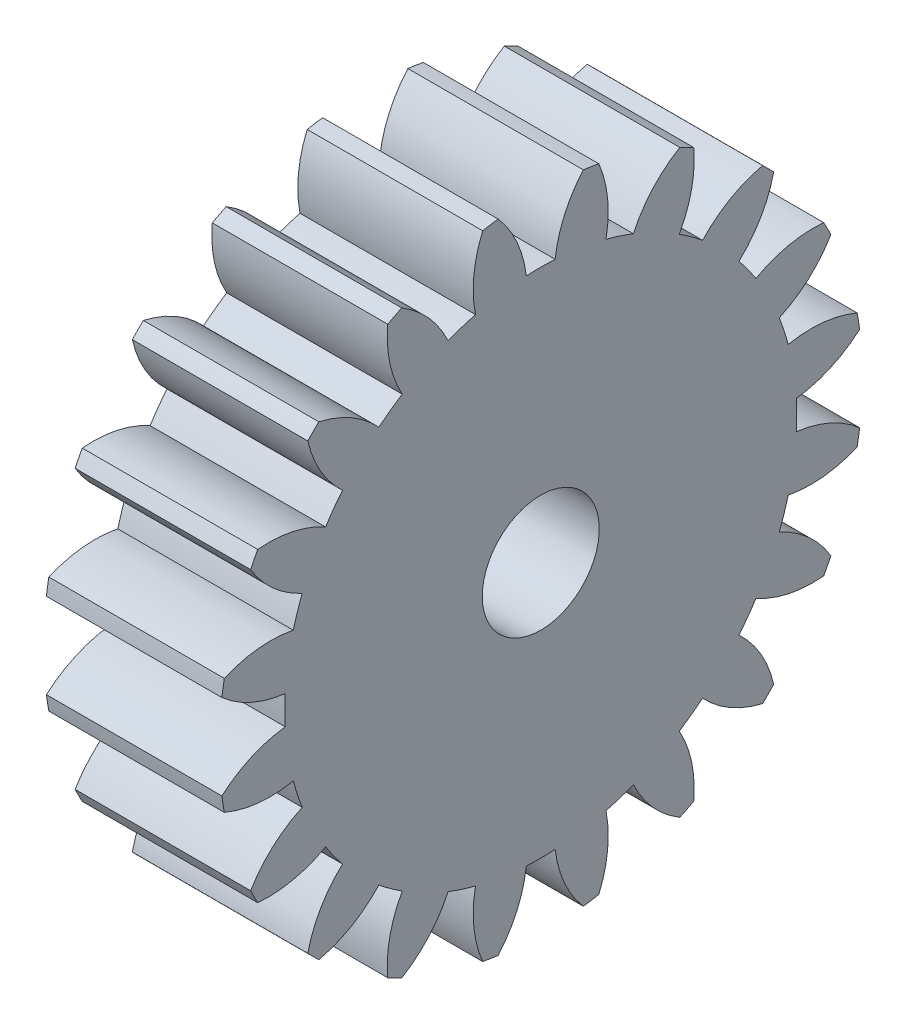
SolidWorks part; units mm, degrees
ref_plane "Plane1" through (0, 0, 0) normal (0, 0, 1) x (1, 0, 0)
ref_plane "Plane2" through (0, 0, 0) normal (0, 1, 0) x (1, 0, 0)
ref_plane "Plane3" through (0, 0, 0) normal (1, 0, 0) x (0, 0, -1)
sketch "HoldingSke" plane through (0, 0, 0) normal (0, 1, 0) x (1, 0, 0)
  line L0 (0, 0) -> (0.1879, -0.0684)
  line L1 (-15, 0) -> (100, 0) construction
  line L2 (0, 0) -> (-2.1039, 2.3779)
  line L3 (0, 0) -> (-11.863, 4.5341)
  line L4 (0, 0) -> (8.1152, 2.9537)
  line L5 (0, 0) -> (-46.8476, -17.4728)
  line L6 (0, 0) -> (-24.8689, -16.7791)
  line L7 (-2.1039, 2.3779) -> (8.6586, 51.2059)
  line L8 (-76.2, 54.61) -> (-73.4, 54.61)
  line L9 (-71.009, 38.7566) -> (-53.1078, 45.2721)
  line L10 (-76.2, 71.12) -> (104.1128, 71.12)
  line L11 (0, 0) -> (-30, 0)
  line L12 (-76.2, 101.6) -> (-76.033, 101.6)
  line L13 (24.9733, 27.94) -> (52.9518, 28.4284)
  line L14 (24.9733, 27.94) -> (24.9743, 27.94)
  line L15 (24.9733, 27.94) -> (100.4006, 29.5858)
  line L16 (-63.627, -5) -> (-12.827, -5)
  circle A0 centre (0, 0) radius 10
  circle A1 centre (0, 0) radius 37.5
  circle A2 centre (0, 0) radius 37.5
  circle A3 centre (0, 0) radius 10
  dimension "MHD" = 75
  dimension "Hub_dia" = 75
  dimension "Bore" = 20
  dimension "MBD" = 20
  dimension "Num_teeth" = 20
  dimension "Pitch" = 0.2
  dimension "Overall_len" = 50
  dimension "Show_teeth" = 20
  dimension "Thickness" = 30
  dimension "OAL" = 50.0001
  dimension "T_dim" = 2.8
  dimension "Ap" = 20
  dimension "H" = 19.05
  dimension "Pitch_radius" = 180.3128
  dimension "Width" = 30
  dimension "Backlash" = 0.167
  dimension "Addendum_fac" = 1
  dimension "Dedendum_fac" = 1.25
  dimension "Clearance_fac" = 0.25
  dimension "Dedendum_add" = 0.001
  dimension "Module" = 5
sketch "BasProSke" plane through (0, 0, 0) normal (0, 1, 0) x (1, 0, 0)
  line L0 (-10, 0) -> (60, 0) construction
  line L1 (0, 0) -> (0, 55)
  line L2 (0, 0) -> (30, 0)
  line L3 (30, 0) -> (30, 55)
  line L4 (30, 55) -> (0, 55)
  dimension "Thickness" = 30
  dimension "Diameter" = 110
revolve "Base-Revolve" add sketch "BasProSke" angle 360 about L0
sketch "TooCutSke" plane through (0, 0, 0) normal (1, 0, 0) x (0, 0, -1)
  line L1 (0, 0) -> (0, 107) construction
  line L2 (0, 0) -> (-4.2151, 49.822) construction
  line L3 (0, 0) -> (-15.6021, 98.5081) construction
  line L4 (-4.2151, 49.822) -> (-7.8011, 49.254) construction
  arc A0 (2.4648, 43.6795) -> (-2.4648, 43.6795) centre (0, 0) ccw
  arc A1 (7.3009, 54.5389) -> (-7.3009, 54.5389) centre (0, 0) ccw
  circle A2 centre (0, 0) radius 50 construction
  circle A3 centre (0, 0) radius 46.9846 construction
  arc A4 (-2.4648, 43.6795) -> (-7.3009, 54.5389) centre (-22.3276, 41.3405) ccw
  arc A5 (7.3009, 54.5389) -> (2.4648, 43.6795) centre (22.3276, 41.3405) ccw
  dimension "Root_dia" = 87.498
  dimension "Overcut_dia" = 110.0508
  dimension "Pitch_dia" = 100
  dimension "Base_dia" = 93.9693
  dimension "Flank_rad" = 20
  dimension "Half_ang" = 9
  dimension "Half_CT" = 3.6307
extrude "ToothCut" cut sketch "TooCutSke" along normal through all
fillet "Breaks" [suppressed] radius 0.1
fillet "RootFillets" [suppressed] radius 1.251
pattern_circular "TeethCuts" count 20 every 18 about axis through (-10, 0, 0) along (1, 0, 0) of "ToothCut", "RootFillets", "Breaks"
sketch "HubNeaOneSke" plane through (0, 0, 0) normal (-1, 0, 0) x (0, 0, 1)
  circle A0 centre (0, 0) radius 37.5
  dimension "Diameter" = 75
extrude "HubNearOne" [suppressed] add sketch "HubNeaOneSke" along normal blind 20.0001
sketch "HubNeaBotSke" plane through (0, 0, 0) normal (-1, 0, 0) x (0, 0, 1)
  circle A0 centre (0, 0) radius 37.5
  dimension "Diameter" = 75
extrude "HubNearBoth" [suppressed] add sketch "HubNeaBotSke" along normal blind 10
ref_plane "FarPln" through (30, 0, 0) normal (1, 0, 0) x (0, 0, -1)
sketch "HubFarSke" plane through (30, 0, 0) normal (1, 0, 0) x (0, 0, -1)
  circle A0 centre (0, 0) radius 37.5
  dimension "Diameter" = 75
extrude "HubFar" [suppressed] add sketch "HubFarSke" along normal blind 10
sketch "BorSke" plane through (0, 0, 0) normal (1, 0, 0) x (0, 0, -1)
  circle A0 centre (0, 0) radius 10
  dimension "Diameter" = 20
extrude "Bore" cut sketch "BorSke" along normal mid plane 100.0001
sketch "KeySke" plane through (0, 0, 0) normal (1, 0, 0) x (0, 0, -1)
  line L0 (-3, 0) -> (-3, 12.8)
  line L1 (-3, 12.8) -> (3, 12.8)
  line L2 (3, 12.8) -> (3, 0)
  line L3 (0, 0) -> (0, 34) construction
  line L4 (-3, 0) -> (3, 0)
  dimension "Offset" = 12.8
  dimension "Width" = 6
extrude "Keyway" [suppressed] cut sketch "KeySke" along normal mid plane 100.0001
pattern_circular "Keyway2" [suppressed] count 2 every 90 about axis through (-10, 0, 0) along (1, 0, 0)
equation "' \"Module@HoldingSke\" = 6.35"
equation "' \"Num_teeth@HoldingSke\" = 12"
equation "' \"Ap@HoldingSke\" =  20"
equation "' \"Ap@HoldingSke\" = 20"
equation "' \"Width@HoldingSke\" = 0.5 * 25.4"
equation "' \"Hub_dia@HoldingSke\"= 1 * 25.4"
equation "' \"Hub_dia@HoldingSke\" = 1 * 25.4"
equation "' \"Overall_len@HoldingSke\" = 1.0 * 25.4"
equation "' \"Bore@HoldingSke\" = 0.75 * 25.4"
equation "' \"T_dim@HoldingSke\" = 0.1 * 25.4"
equation "' \"Width@KeySke\" = 0.25 * 25.4"
equation "' \"Show_teeth@HoldingSke\" = 13"
equation "' \"Backlash@HoldingSke\" = 0.009 * 25.4"
equation "' \"Addendum_fac@HoldingSke\" = 1.0"
equation "' \"Dedendum_fac@HoldingSke\" = 1.25"
equation "' \"Dedendum_add@HoldingSke\" = 0.00005 * 25.4"
equation "' \"Clearance_fac@HoldingSke\" = 0.25"
equation "\"Pitch@HoldingSke\" = 1 / \"Module@HoldingSke\""
equation "\"Overcut_dia@TooCutSke\" = (\"Num_teeth@HoldingSke\" + 2 * \"Addendum_fac@HoldingSke\") / \"Pitch@HoldingSke\" + 0.002 * 25.4"
equation "\"Pitch_dia@TooCutSke\" = \"Num_teeth@HoldingSke\" / \"Pitch@HoldingSke\""
equation "\"Base_dia@TooCutSke\" = \"Num_teeth@HoldingSke\" / \"Pitch@HoldingSke\" * cos((\"Ap@HoldingSke\"  * 3.14159265 / 180))"
equation "\"Root_dia@TooCutSke\" = (\"Num_teeth@HoldingSke\" + 2) / \"Pitch@HoldingSke\" - 2 * (\"Addendum_fac@HoldingSke\" + \"Dedendum_fac@HoldingSke\") / \"Pitch@HoldingSke\" - \"Dedendum_add@HoldingSke\" * 2"
equation "\"Half_ang@TooCutSke\" = 180 / \"Num_teeth@HoldingSke\""
equation "\"Half_CT@TooCutSke\" = \"Num_teeth@HoldingSke\" / \"Pitch@HoldingSke\" * sin((3.14159265 / 2 / \"Num_teeth@HoldingSke\")) / 2 - 7 * \"Backlash@HoldingSke\" / 4"
equation "\"Flank_rad@TooCutSke\" = \"Num_teeth@HoldingSke\" / \"Pitch@HoldingSke\" / 5"
equation "\"Radius@RootFillets\" = \"Clearance_fac@HoldingSke\" / \"Pitch@HoldingSke\" + \"Dedendum_add@HoldingSke\""
equation "\"Break_rad@Breaks\" = 0.02 / \"Pitch@HoldingSke\""
equation "\"Thickness@HoldingSke\" = \"Width@HoldingSke\""
equation "\"OAL@HoldingSke\" = \"Thickness@HoldingSke\""
equation "\"MHD@HoldingSke\" = (\"Num_teeth@HoldingSke\" + 2) / \"Pitch@HoldingSke\" - 2 * (\"Addendum_fac@HoldingSke\" + \"Dedendum_fac@HoldingSke\")  / \"Pitch@HoldingSke\" - \"Dedendum_add@HoldingSke\" * 2"
equation "\"MBD@HoldingSke\" = (\"Num_teeth@HoldingSke\" + 2) / \"Pitch@HoldingSke\" - 2 * (\"Addendum_fac@HoldingSke\" + \"Dedendum_fac@HoldingSke\")  / \"Pitch@HoldingSke\" - \"Dedendum_add@HoldingSke\" * 2 - 0.002 * 25.4"
equation "\"MHD@HoldingSke\" = ((sgn( \"MHD@HoldingSke\" - \"Hub_dia@HoldingSke\" )-1)*( \"MHD@HoldingSke\" - \"Hub_dia@HoldingSke\" ))/-2+ \"Hub_dia@HoldingSke\""
equation "\"MBD@HoldingSke\" = ((sgn( \"MBD@HoldingSke\" - \"Bore@HoldingSke\" )-1)*( \"MBD@HoldingSke\" - \"Bore@HoldingSke\" ))/-2+ \"Bore@HoldingSke\""
equation "\"OAL@HoldingSke\" = ((sgn( \"OAL@HoldingSke\" - \"Overall_len@HoldingSke\" )+1)*( \"OAL@HoldingSke\" - \"Overall_len@HoldingSke\" ))/2 + \"Overall_len@HoldingSke\" + 0.000002 * 25.4"
equation "\"Num_teeth@TeethCuts\" = int( \"Show_teeth@HoldingSke\" ) + 1"
equation "\"Num_teeth@TeethCuts\" = ((sgn( \"Num_teeth@TeethCuts\" - \"Num_teeth@HoldingSke\" )-1)*( \"Num_teeth@TeethCuts\" - \"Num_teeth@HoldingSke\" ))/-2+ \"Num_teeth@HoldingSke\""
equation "\"Num_teeth@TeethCuts\" = ((sgn( \"Num_teeth@TeethCuts\" - 2.0)+1)*( \"Num_teeth@TeethCuts\" - 2.0))/2 +2.0"
equation "\"Angle@TeethCuts\" = 360.0 / \"Num_teeth@HoldingSke\""
equation "\"Diameter@BasProSke\" = (\"Num_teeth@HoldingSke\" + 2 * \"Addendum_fac@HoldingSke\") / \"Pitch@HoldingSke\""
equation "\"Thickness@BasProSke\"  = \"Thickness@HoldingSke\""
equation "' \"Fillet_rad@BasProSke\" =  \"Thickness@HoldingSke\" * 0.05"
equation "' \"Fillet_rad@BasProSke\" = \"Thickness@HoldingSke\" * 0.05"
equation "\"MHD@HoldingSke\" = ((sgn( \"MHD@HoldingSke\" - \"Root_dia@TooCutSke\" )-1)*( \"MHD@HoldingSke\" - \"Root_dia@TooCutSke\" ))/-2+ \"Root_dia@TooCutSke\""
equation "\"Diameter@HubNeaOneSke\" = \"MHD@HoldingSke\""
equation "\"Length@HubNearOne\" = \"OAL@HoldingSke\" - \"Thickness@BasProSke\""
equation "\"Diameter@HubNeaBotSke\" = \"MHD@HoldingSke\""
equation "\"Length@HubNearBoth\" = ( \"OAL@HoldingSke\" - \"Thickness@BasProSke\" ) / 2.0"
equation "\"Thickness@FarPln\" = \"Thickness@BasProSke\""
equation "\"Diameter@HubFarSke\" = \"MHD@HoldingSke\""
equation "\"Length@HubFar\" = ( \"OAL@HoldingSke\" - \"Thickness@BasProSke\" ) / 2.0"
equation "\"Diameter@BorSke\" = \"MBD@HoldingSke\""
equation "\"D1@Bore\" = \"OAL@HoldingSke\" * 2.0"
equation "\"D1@Keyway\" = \"OAL@HoldingSke\" * 2.0"
equation "\"Offset@KeySke\" = \"T_dim@HoldingSke\" + \"MBD@HoldingSke\" / 2.0"
